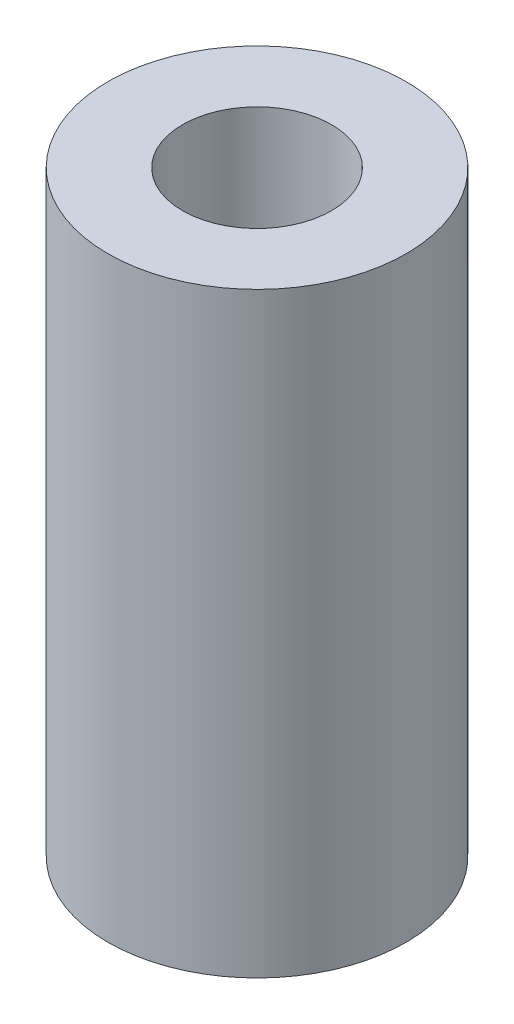
SolidWorks part; units mm, degrees
ref_plane "Plan de face" through (0, 0, 0) normal (0, 0, 1) x (1, 0, 0)
ref_plane "Plan de dessus" through (0, 0, 0) normal (0, 1, 0) x (1, 0, 0)
ref_plane "Plan de droite" through (0, 0, 0) normal (1, 0, 0) x (0, 0, -1)
sketch "Esquisse1" plane through (0, 0, 0) normal (0, 1, 0) x (1, 0, 0)
  circle A0 centre (0, 0) radius 4
extrude "Boss.-Extru.1" add sketch "Esquisse1" along normal blind 16
sketch "Esquisse2" plane through (0, 16, 0) normal (0, 1, 0) x (1, 0, 0)
  circle A0 centre (0, 0) radius 2
extrude "Enlèv. mat.-Extru.1" cut sketch "Esquisse2" against normal up to next
